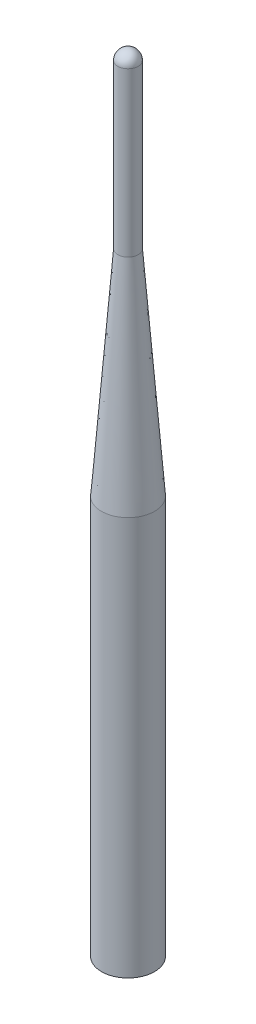
SolidWorks part; units mm, degrees
ref_plane "Front Plane" through (0, 0, 0) normal (0, 0, 1) x (1, 0, 0)
ref_plane "Top Plane" through (0, 0, 0) normal (0, 1, 0) x (1, 0, 0)
ref_plane "Right Plane" through (0, 0, 0) normal (1, 0, 0) x (0, 0, -1)
sketch "Sketch1" plane through (0, 0, 0) normal (0, 1, 0) x (1, 0, 0)
  circle A0 centre (0, 0) radius 6.5
  dimension "D1" = 13
extrude "Boss-Extrude2" add sketch "Sketch1" along normal blind 22.75
sketch "Sketch2" plane through (0, 0, 0) normal (0, 0, 1) x (1, 0, 0)
  line L0 (0, 22.75) -> (0, 192.75) construction
  line L1 (6.5, 22.75) -> (-6.5, 22.75) construction
  line L2 (0, 22.75) -> (-6.5, 22.75)
  line L3 (-6.5, 22.75) -> (-6.5, 97.75)
  line L4 (-6.5, 97.75) -> (-2.51, 150.25)
  line L5 (-2.51, 150.25) -> (-2.51, 190.25)
  line L6 (-0.01, 192.75) -> (0, 192.75)
  line L7 (0, 22.75) -> (0, 192.75)
  arc A0 (-2.51, 190.25) -> (-0.01, 192.75) centre (-0.01, 190.25) cw
  dimension "D2" = 2.5
  dimension "D1" = 75
  dimension "D3" = 2.51
  dimension "D4" = 95
  dimension "D5" = 40
revolve "Revolve1" add sketch "Sketch2" angle 360 about L0
equation "\"D4@Sketch2\"=170mm - \"D1@Sketch2\" "
